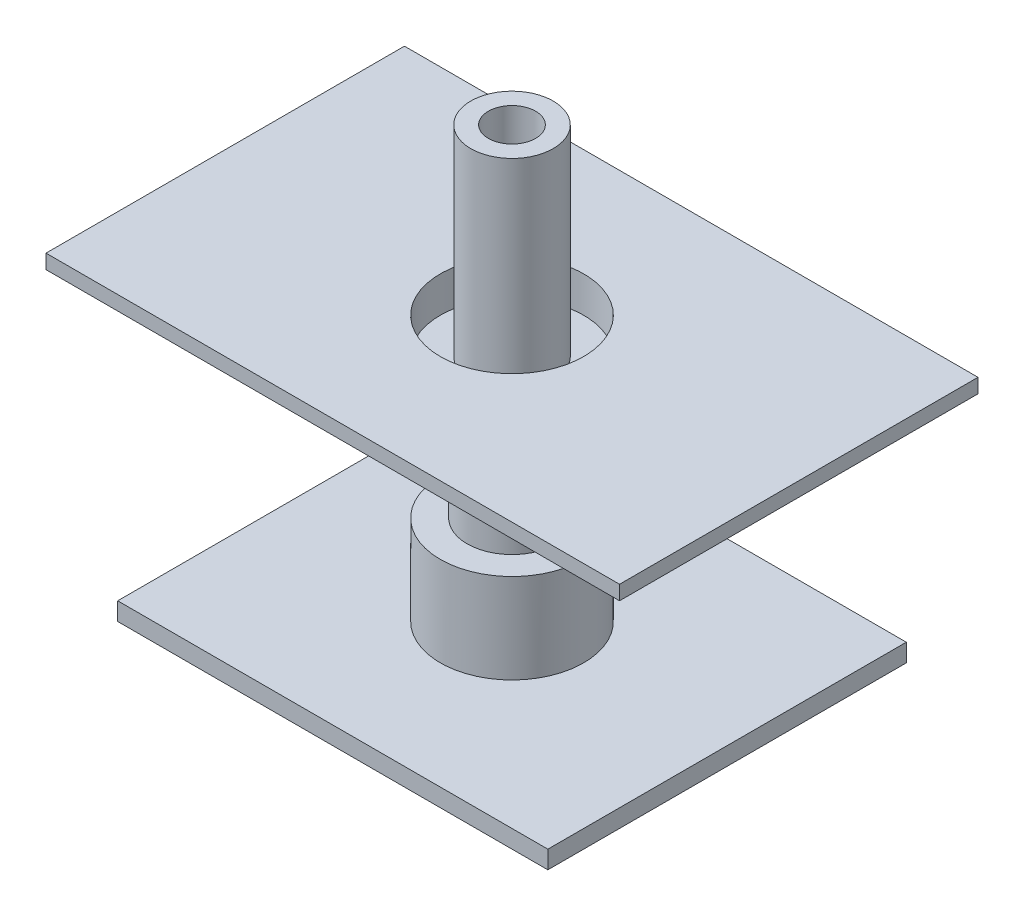
SolidWorks part; units mm, degrees
ref_plane "Front Plane" through (0, 0, 0) normal (0, 0, 1) x (1, 0, 0)
ref_plane "Top Plane" through (0, 0, 0) normal (0, 1, 0) x (1, 0, 0)
ref_plane "Right Plane" through (0, 0, 0) normal (1, 0, 0) x (0, 0, -1)
sketch "Sketch1" plane through (0, 0, 0) normal (0, 1, 0) x (1, 0, 0)
  line L1 (-60, -50) -> (60, -50)
  line L2 (-60, -50) -> (-60, 50)
  line L3 (-60, 50) -> (60, 50)
  line L4 (60, -50) -> (60, 50)
  line L5 (-60, -50) -> (60, 50) construction
  line L6 (-60, 50) -> (60, -50) construction
  point P0 (0, 0)
  dimension "D1" = 100
  dimension "D2" = 120
extrude "Boss-Extrude1" add sketch "Sketch1" along normal blind 5
sketch "Sketch2" plane through (0, 5, 0) normal (0, 1, 0) x (1, 0, 0)
  circle A0 centre (0, 0) radius 20
  circle A1 centre (0, 0) radius 12.5
  dimension "D1" = 40
  dimension "D2" = 25
extrude "Boss-Extrude2" add sketch "Sketch2" along normal blind 25
sketch "Sketch4" plane through (0, 5, 0) normal (0, 1, 0) x (1, 0, 0)
  circle A0 centre (0, 0) radius 12.5
extrude "Boss-Extrude3" add sketch "Sketch4" along normal blind 60 separate body
sketch "Sketch5" plane through (0, 65, 0) normal (0, 1, 0) x (1, 0, 0)
  circle A0 centre (0, 0) radius 6.5869
extrude "Cut-Extrude1" cut sketch "Sketch5" against normal blind 30
sketch "Sketch9" plane through (0, 65, 0) normal (0, 1, 0) x (1, 0, 0)
  circle A0 centre (0, 0) radius 6.5869
  circle A1 centre (0, 0) radius 11.5
  dimension "D1" = 23
extrude "Boss-Extrude6" add sketch "Sketch9" along normal blind 60
sketch "Sketch6" plane through (0, 65, 0) normal (0, 1, 0) x (1, 0, 0)
  line L1 (-80, -50) -> (80, -50)
  line L2 (-80, -50) -> (-80, 50)
  line L3 (-80, 50) -> (80, 50)
  line L4 (80, -50) -> (80, 50)
  line L5 (-80, -50) -> (80, 50) construction
  line L6 (-80, 50) -> (80, -50) construction
  circle A0 centre (0, 0) radius 12.5
  point P0 (0, 0)
  dimension "D1" = 25
  dimension "D2" = 160
  dimension "D3" = 100
extrude "Boss-Extrude4" add sketch "Sketch6" along normal blind 4 from offset 10 separate body
sketch "Sketch7" plane through (0, 65, 0) normal (0, 1, 0) x (-1, 0, 0)
  circle A0 centre (0, 0) radius 25
  dimension "D2" = 50
sketch "Sketch10" plane through (0, 79, 0) normal (0, 1, 0) x (1, 0, 0)
  circle A0 centre (0, 0) radius 22.5
  circle A2 centre (0, 0) radius 11.5
extrude "Boss-Extrude7" add sketch "Sketch10" against normal up to surface (14 mm away) up to face at (0, 65, 11.5)
sketch "Sketch8" plane through (0, 79, 0) normal (0, 1, 0) x (1, 0, 0)
  circle A1 centre (0, 0) radius 20
  circle A2 centre (0, 0) radius 11.5
  dimension "D2" = 40
extrude "Cut-Extrude5" cut sketch "Sketch8" against normal blind 10
